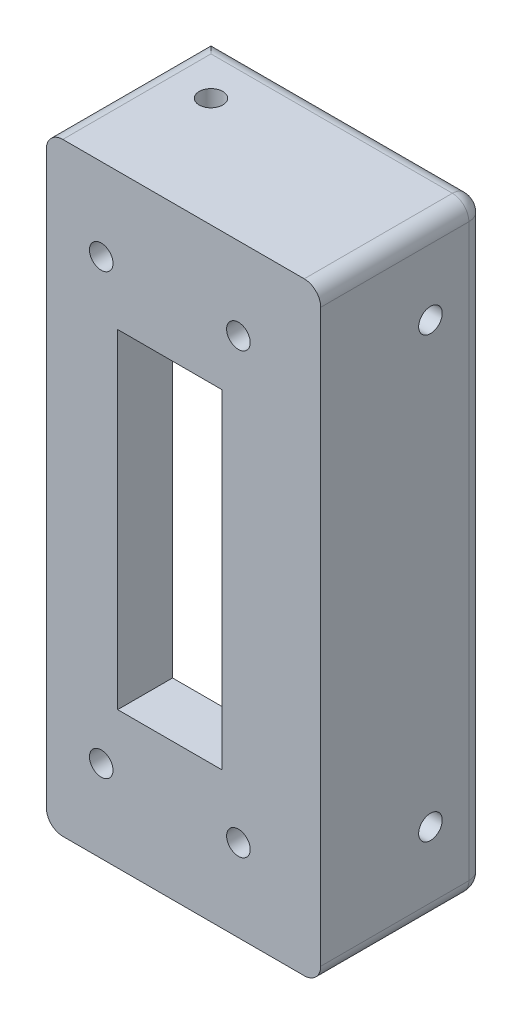
SolidWorks part; units mm, degrees
material "ABS"
ref_plane "Ebene vorne" through (0, 0, 0) normal (0, 0, 1) x (1, 0, 0)
ref_plane "Ebene oben" through (0, 0, 0) normal (0, 1, 0) x (1, 0, 0)
ref_plane "Ebene rechts" through (0, 0, 0) normal (1, 0, 0) x (0, 0, -1)
sketch "Skizze1" plane through (0, 0, 0) normal (0, 0, 1) x (1, 0, 0)
  line L0 (0, 0) -> (45, 0)
  line L1 (45, 0) -> (45, 100)
  line L2 (45, 100) -> (0, 100)
  line L3 (0, 100) -> (0, 0)
  line L4 (0, 0) -> (0, 10)
  line L5 (0, 10) -> (10, 10)
  line L6 (45, 0) -> (45, 10)
  line L7 (45, 10) -> (35, 10)
  line L8 (0, 100) -> (0, 90)
  line L9 (0, 90) -> (10, 90)
  line L10 (45, 100) -> (45, 90)
  line L11 (45, 90) -> (35, 90)
  line L12 (0, 10) -> (0, 20)
  line L13 (0, 20) -> (45, 20)
  line L14 (0, 90) -> (0, 80)
  line L15 (0, 80) -> (45, 80)
  line L16 (45, 80) -> (32, 80)
  line L17 (32, 80) -> (32, 20)
  line L18 (0, 80) -> (13, 80)
  line L19 (13, 80) -> (13, 20)
  line L20 (45, 0) -> (50, 0)
  line L21 (50, 0) -> (50, 100)
  line L22 (50, 100) -> (45, 100)
  line L23 (50, 100) -> (50, 105)
  line L24 (50, 105) -> (0, 105)
  line L25 (0, 105) -> (0, 100)
  line L26 (50, 0) -> (50, -5)
  line L27 (50, -5) -> (0, -5)
  line L28 (0, -5) -> (0, 0)
  circle A0 centre (10, 10) radius 2.15
  circle A1 centre (35, 10) radius 2.15
  circle A2 centre (10, 90) radius 2.15
  circle A3 centre (35, 90) radius 2.15
  dimension "D5" = 10
  dimension "D6" = 4.3
  dimension "D7" = 4.3
  dimension "D8" = 10
  dimension "D10" = 4.3
  dimension "D13" = 4.3
  dimension "D1" = 45
  dimension "D2" = 100
  dimension "D3" = 10
  dimension "D4" = 10
  dimension "D9" = 10
  dimension "D11" = 10
  dimension "D12" = 10
  dimension "D14" = 10
  dimension "D15" = 10
  dimension "D16" = 13
  dimension "D17" = 13
  dimension "D18" = 5
  dimension "D19" = 5
  dimension "D20" = 5
extrude "Aufsatz-Linear austragen2" add sketch "Skizze1" along normal blind 10
sketch "Skizze3" plane through (0, 0, 0) normal (0, 0, -1) x (-1, 0, 0)
  line L0 (-50, 105) -> (-45, 105)
  line L1 (-50, 105) -> (0, 105) construction
  line L2 (-50, -5) -> (-50, 105) construction
  line L3 (-45, 105) -> (-45, -5)
  line L4 (-50, -5) -> (0, -5) construction
  line L5 (-45, -5) -> (-50, -5)
  line L6 (-50, -5) -> (-50, 105)
  line L7 (-45, 105) -> (0, 105)
  line L8 (0, 105) -> (0, -5) construction
  line L9 (0, 105) -> (0, 100)
  line L10 (0, 100) -> (-45, 100)
  line L11 (-45, -5) -> (0, -5)
  line L12 (0, -5) -> (0, 0)
  line L13 (0, 0) -> (-45, 0)
  line M5 (0, 105) -> (-50, 105)
  line M6 (-50, 105) -> (-50, -5)
  line M7 (-50, -5) -> (0, -5)
  line M8 (0, -5) -> (0, 105)
  dimension "D1" = 5
  dimension "D2" = 45
extrude "Aufsatz-Linear austragen3" add sketch "Skizze3" along normal blind 20 contours L3 M5 M6 M7 | L10 L3 M8 M5 | L13 L3 M8 M7
sketch "Skizze4" plane through (45, 0, 0) normal (-1, 0, 0) x (0, 0, 1)
  line L0 (-20, 100) -> (-20, 90)
  line L1 (-20, 100) -> (-20, 0) construction
  line L2 (-20, 90) -> (-10, 90)
  line L3 (-20, 0) -> (-20, 10)
  line L4 (-20, 10) -> (-10, 10)
  circle A0 centre (-10, 90) radius 2.15
  circle A1 centre (-10, 10) radius 2.15
  dimension "D3" = 4.3
  dimension "D6" = 4.3
  dimension "D1" = 10
  dimension "D2" = 10
  dimension "D4" = 10
  dimension "D5" = 10
extrude "Schnitt-Linear austragen1" cut sketch "Skizze4" against normal blind 20 contours A0 | A1
sketch "Skizze5" plane through (0, 105, 0) normal (0, 1, 0) x (1, 0, 0)
  line L0 (0, 20) -> (10, 20)
  line L1 (0, 20) -> (50, 20) construction
  line L2 (10, 20) -> (10, 10)
  circle A0 centre (10, 10) radius 2.15
  dimension "D1" = 10
  dimension "D3" = 4.3
  dimension "D2" = 10
extrude "Schnitt-Linear austragen2" cut sketch "Skizze5" against normal blind 120 contours A0
fillet "Verrundung1" radius 3 7 edges at (0, -5, -5) (25, -5, -20) (50, -5, -5) (25, 105, -20) (0, 105, -5) (50, 105, -5) (50, 50, -20)
equation "\"M4_mutter\"= 7.4mm"
equation "\"M4_loch\"= 4.3mm"
equation "\"M8_loch\"= 8.4mm"
equation "\"D7@Skizze1\"=\"M4_loch\""
equation "\"D6@Skizze1\"=\"M4_loch\""
equation "\"D10@Skizze1\"=\"M4_loch\""
equation "\"D13@Skizze1\"=\"M4_loch\""
equation "\"D3@Skizze5\"=\"M4_loch\""
equation "\"D3@Skizze4\"=\"M4_loch\""
equation "\"D6@Skizze4\"=\"M4_loch\""
